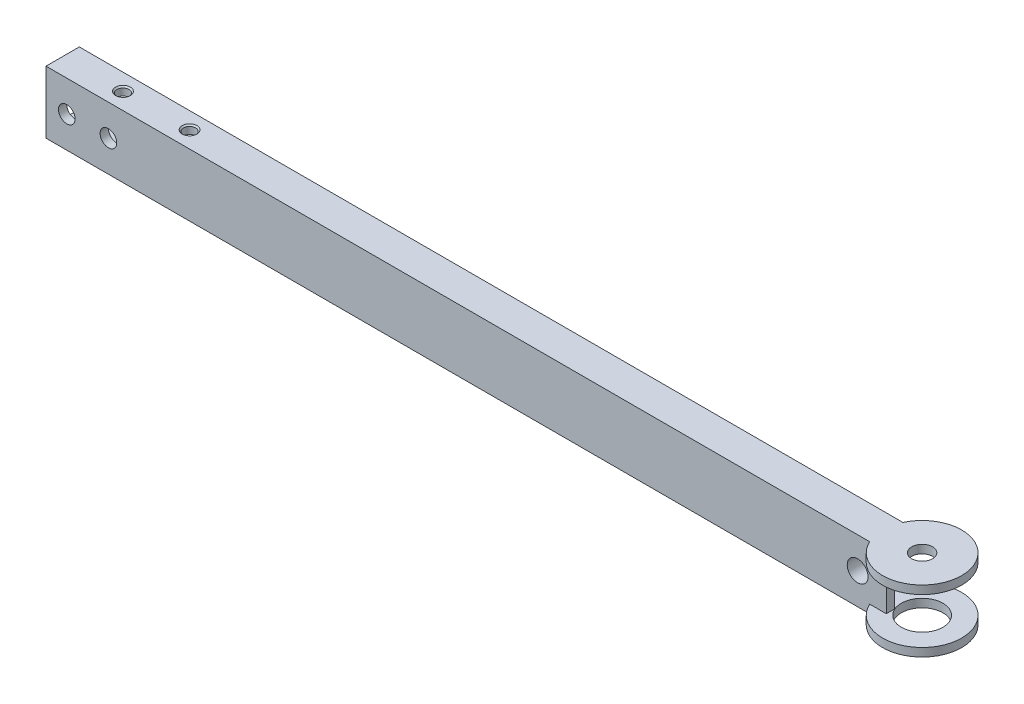
SolidWorks part; units mm, degrees
ref_plane "Front Plane" through (0, 0, 0) normal (0, 0, 1) x (1, 0, 0)
ref_plane "Top Plane" through (0, 0, 0) normal (0, 1, 0) x (1, 0, 0)
ref_plane "Right Plane" through (0, 0, 0) normal (1, 0, 0) x (0, 0, -1)
sketch "Sketch1" plane through (0, 0, 0) normal (0, 1, 0) x (1, 0, 0)
  line L0 (-206.5, 4) -> (-8.6168, 4)
  line L1 (-206.5, 4) -> (-206.5, -4)
  line L2 (-8.6168, -4) -> (-206.5, -4)
  arc A0 (-8.6168, -4) -> (-8.6168, 4) centre (0, 0) ccw
  circle A1 centre (0, 0) radius 5
  point P7 (-9.5, 0)
  point P8 (-206.5, 0)
  point P9 (-192, 0)
  point P10 (-176, 0)
  dimension "D2" = 19
  dimension "D3" = 10
  dimension "D1" = 8
  dimension "D4" = 14.5
  dimension "D5" = 16
  dimension "D6" = 176
extrude "Boss-Extrude3" add sketch "Sketch1" along normal blind 2
sketch "Sketch5" plane through (-206.5, 0, 0) normal (-1, 0, 0) x (0, 0, 1)
  line L1 (4, 2) -> (2, 2)
  line L2 (4, 2) -> (4, 13)
  line L3 (4, 13) -> (2, 13)
  line L4 (2, 2) -> (2, 13)
  dimension "D1" = 2
  dimension "D2" = 11
extrude "Boss-Extrude4" add sketch "Sketch5" against normal up to vertex (197.8832 mm away) up to point (-8.6168, 2, 4)
sketch "Sketch6" plane through (0, 13, 0) normal (0, 1, 0) x (1, 0, 0)
  line L1 (-206.5, 4) -> (-8.6168, 4)
  line L2 (-206.5, 4) -> (-206.5, -4)
  line L3 (-206.5, -4) -> (-8.6168, -4)
  arc A0 (-8.6168, 4) -> (-8.6168, -4) centre (0, 0) cw
  circle A1 centre (0, 0) radius 2.5
  point P7 (-192, 0)
  point P10 (-176, 0)
  point P11 (-206.5, 0)
  dimension "D1" = 5
  dimension "D2" = 16
  dimension "D3" = 14.5
extrude "Boss-Extrude5" add sketch "Sketch6" along normal blind 2
sketch "Sketch8" plane through (-8.6168, 0, 0) normal (1, 0, 0) x (0, 0, -1)
  line L4 (-4, 13) -> (-4, 2)
  line L5 (-4, 2) -> (-2, 2)
  line L6 (-2, 2) -> (-2, 13)
  line L7 (-2, 13) -> (-4, 13)
  line L8 (-4, 13) -> (-4, 2)
  line L9 (-4, 2) -> (-2, 2)
  line L10 (-2, 2) -> (-2, 13)
  line L11 (-2, 13) -> (-4, 13)
  dimension "D1" = 0
extrude "Boss-Extrude6" add sketch "Sketch8" along normal blind 4
sketch "Sketch10" plane through (0, 0, 2) normal (0, 0, -1) x (-1, 0, 0)
  line L0 (206.5, 15) -> (206.5, 0) construction
  line L1 (206.5, 0) -> (8.6168, 0) construction
  circle A0 centre (201.5, 7.5) radius 2
  circle A1 centre (191.5, 7.5) radius 2
  dimension "D3" = 4
  dimension "D4" = 4
  dimension "D1" = 5
  dimension "D2" = 10
  dimension "D9" = 7.5
extrude "Cut-Extrude8" cut sketch "Sketch10" against normal up to next
sketch "Sketch11" plane through (0, 0, 2) normal (0, 0, -1) x (-1, 0, 0)
  line L0 (206.5, 13) -> (206.5, 2) construction
  line L3 (8.6168, 0) -> (206.5, 0) construction
  circle A0 centre (11.5, 7.5) radius 4
  circle A1 centre (11.5, 7.5) radius 2.5
  dimension "D1" = 8
  dimension "D2" = 5
  dimension "D3" = 195
  dimension "D4" = 7.5
extrude "Boss-Extrude7" add sketch "Sketch11" along normal blind 4
sketch "Sketch12" plane through (0, 0, 2) normal (0, 0, -1) x (-1, 0, 0)
  circle A2 centre (11.5, 7.5) radius 2.5
  circle A3 centre (11.5, 7.5) radius 2.5
  dimension "D1" = 0
extrude "Cut-Extrude9" cut sketch "Sketch12" against normal up to next
fillet "Fillet1" radius 1 1 edges at (-15.5, 7.5, 2)
hole_wizard "M3.5x0.6 Tapped Hole7" positions "Sketch21" profile "Sketch23" tap size "M3.5x0.6" standard "ANSI Metric"
sketch "Sketch21" plane through (0, 15, 0) normal (0, 1, 0) x (1, 0, 0)
  point P0 (-176, 0)
  point P3 (-192, 0)
sketch "Sketch23" plane through (-176, 15, 0) normal (1, 0, 0) x (0, 0, 1)
  line L0 (0, 0) -> (0, 2)
  line L1 (0, 2) -> (1.45, 2)
  line L2 (1.45, 2) -> (1.45, 0.325)
  line L3 (1.45, 0.325) -> (1.775, 0)
  line L5 (1.775, 0) -> (0, 0)
  line L6 (-1.45, 0.325) -> (-1.775, 0) construction
  line L11 (0, -6.35) -> (0, 107.95) construction
  dimension "Thru Tap Drill Dia." = 2.9
  dimension "Thru Tap Drill Depth" = 2
  dimension "Near C'Sink Dia." = 3.55
  dimension "Near C'Sink Angle" = 90
cosmetic thread "Hole Thread1" parameters "D2"=3.5
cosmetic thread "Hole Thread2" parameters "D2"=3.5
